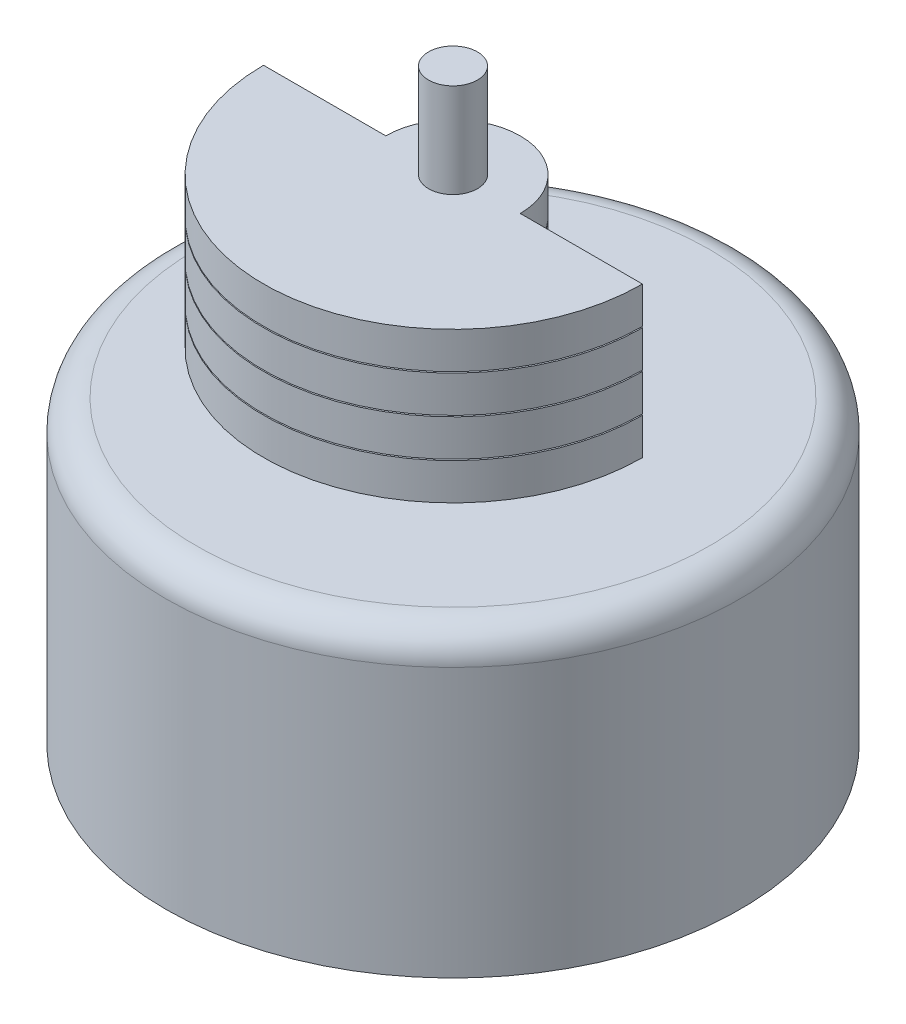
SolidWorks part; units mm, degrees
material "1023 Carbon Steel Sheet (SS)"
ref_plane "Front Plane" through (0, 0, 0) normal (0, 0, 1) x (1, 0, 0)
ref_plane "Top Plane" through (0, 0, 0) normal (0, 1, 0) x (1, 0, 0)
ref_plane "Right Plane" through (0, 0, 0) normal (1, 0, 0) x (0, 0, -1)
sketch "Sketch1" plane through (0, 0, 0) normal (0, 0, 1) x (1, 0, 0)
  line L0 (0, 0) -> (0, -22701.703) construction
  line L1 (0, 0) -> (-11.938, 0)
  line L2 (-11.938, 0) -> (-11.938, 12.446)
  line L3 (-11.938, 12.446) -> (-3.302, 12.446)
  line L4 (0, 13.462) -> (0, 0)
  line L5 (-3.302, 12.446) -> (-3.302, 13.462)
  line L6 (-3.302, 13.462) -> (0, 13.462)
  line L8 (-1.016, 13.462) -> (0, 13.462)
  line L9 (-1.016, 13.462) -> (-1.016, 24.384)
  line L10 (-1.016, 24.384) -> (0, 24.384)
  line L11 (0, 13.462) -> (0, 24.384)
  line L12 (0, 0) -> (-3.048, 0)
  line L13 (0, 0) -> (0, -1.524)
  line L14 (0, -1.524) -> (-3.048, -1.524)
  line L15 (-3.048, 0) -> (-3.048, -1.524)
  dimension "D1" = 23.876
  dimension "D2" = 6.604
  dimension "D3" = 2.032
  dimension "D4" = 6.096
  dimension "D5" = 1.524
  dimension "D6" = 12.446
  dimension "D7" = 1.016
  dimension "D8" = 10.922
revolve "Revolve1" add sketch "Sketch1" angle 360 about L0
fillet "Fillet1" radius 1.27 2 edges at (0, -1.524, 3.048) (0, 12.446, 11.938)
ref_plane "Plane1" through (0, 14.986, 0) normal (0, 1, 0) x (1, 0, 0)
sketch "Sketch2" plane through (0, 14.986, 0) normal (0, 1, 0) x (1, 0, 0)
  line L0 (-7.874, 0) -> (-2.794, 0)
  line L2 (2.794, 0) -> (7.874, 0)
  arc A0 (2.794, 0) -> (-2.794, 0) centre (0, 0) ccw
  arc A1 (-7.874, 0) -> (7.874, 0) centre (0, 0) ccw
  dimension "D1" = 2.794
  dimension "D2" = 7.874
extrude "Boss-Extrude1" add sketch "Sketch2" along normal mid plane 1.524
pattern_linear "LPattern1" count 4 spacing 1.5748 along (0, 1, 0) of "Boss-Extrude1"
